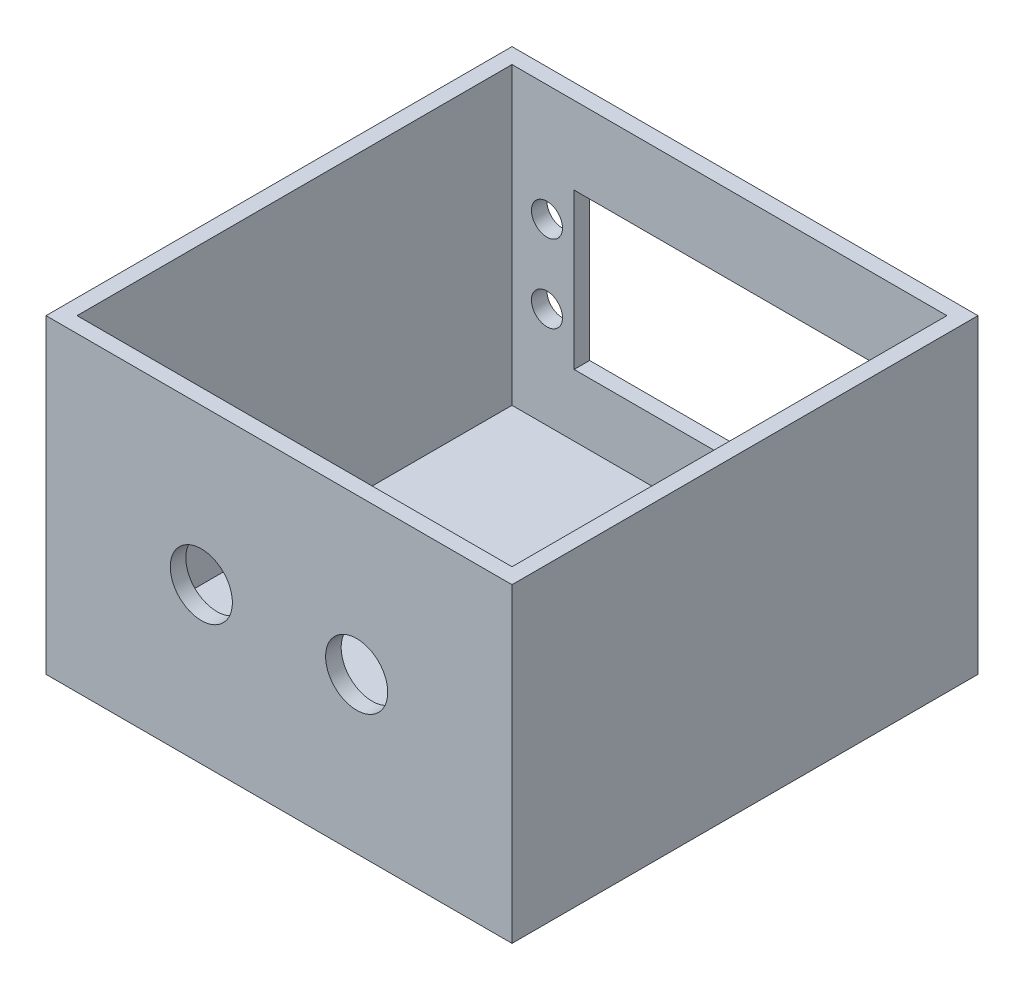
SolidWorks part; units mm, degrees
ref_plane "Ön Düzlem" through (0, 0, 0) normal (0, 0, 1) x (1, 0, 0)
ref_plane "Üst Düzlem" through (0, 0, 0) normal (0, 1, 0) x (1, 0, 0)
ref_plane "Sağ Düzlem" through (0, 0, 0) normal (1, 0, 0) x (0, 0, -1)
sketch "Çizim2" plane through (0, 0, 0) normal (0, 0, 1) x (1, 0, 0)
  line L1 (0, 0) -> (60, 0)
  line L2 (0, 0) -> (0, 40)
  line L3 (0, 40) -> (60, 40)
  line L4 (60, 0) -> (60, 40)
  dimension "D1" = 40
  dimension "D2" = 60
extrude "Yükseklik-Ekstrüzyon1" add sketch "Çizim2" along normal blind 60
shell "İç Boşaltma1" thickness 2
sketch "Çizim4" plane through (0, 0, 0) normal (0, 0, -1) x (-1, 0, 0)
  line L0 (-60, 0) -> (-60, 40) construction
  line L1 (-50, 30) -> (-10, 30)
  line L2 (-50, 30) -> (-50, 10)
  line L3 (-50, 10) -> (-10, 10)
  line L4 (-10, 30) -> (-10, 10)
  line L5 (0, 0) -> (-60, 0) construction
  circle A0 centre (-53.5, 25) radius 2
  circle A1 centre (-53.5, 15) radius 2
  circle A2 centre (-6.5, 15) radius 2
  circle A3 centre (-6.5, 25) radius 2
  dimension "D7" = 4
  dimension "D5" = 4
  dimension "D1" = 40
  dimension "D2" = 20
  dimension "D3" = 10
  dimension "D4" = 10
extrude "Kes-Ekstrüzyon2" cut sketch "Çizim4" against normal up to next
sketch "Çizim5" plane through (0, 0, 0) normal (0, -1, 0) x (1, 0, 0)
  circle A0 centre (30, 30) radius 2
  circle A1 centre (38, 30) radius 2
  circle A2 centre (38, 38) radius 2 [skipped]
  circle A3 centre (30, 38) radius 2
  circle A4 centre (30, 22) radius 2
  circle A5 centre (22, 30) radius 2
  dimension "D1" = 4
  dimension "D4" = 8
  dimension "D5" = 8
  dimension "D2" = 2
  dimension "D3" = 2
extrude "Kes-Ekstrüzyon3" cut sketch "Çizim5" against normal up to next
sketch "Çizim6" plane through (0, 0, 60) normal (0, 0, 1) x (1, 0, 0)
  line L0 (0, 40) -> (0, 0) construction
  line L1 (60, 40) -> (0, 40) construction
  line L2 (30, 40) -> (30, 0) construction
  line L4 (0, 0) -> (60, 0) construction
  circle A0 centre (20, 20) radius 4
  circle A1 centre (40, 20) radius 4
  dimension "D2" = 8
  dimension "D1" = 20
  dimension "D3" = 20
extrude "Kes-Ekstrüzyon4" cut sketch "Çizim6" against normal up to next contours A0 | A1
